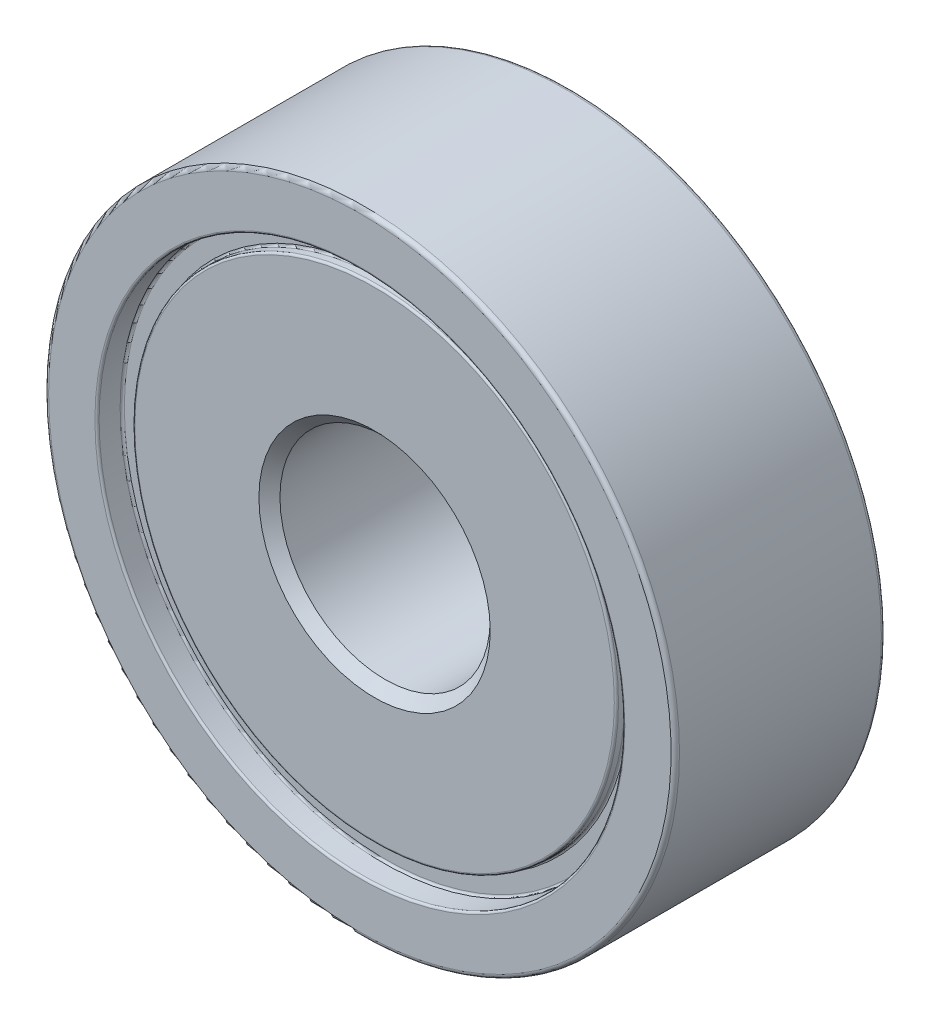
SolidWorks part; units mm, degrees
ref_plane "Front Plane" through (0, 0, 0) normal (0, 0, 1) x (1, 0, 0)
ref_plane "Top Plane" through (0, 0, 0) normal (0, 1, 0) x (1, 0, 0)
ref_plane "Right Plane" through (0, 0, 0) normal (1, 0, 0) x (0, 0, -1)
sketch "Sketch1" plane through (0, 0, 0) normal (1, 0, 0) x (0, 0, -1)
  line L0 (0.07, 0.5) -> (0.07, 1.15)
  line L1 (0.12, 1.15) -> (0.07, 1.15)
  line L2 (0.88, 1.15) -> (0.88, 1.25)
  line L3 (0.12, 1.25) -> (0, 1.25)
  line L4 (0, 1.25) -> (0, 1.5)
  line L5 (0, 1.5) -> (1, 1.5)
  line L6 (1, 1.5) -> (1, 1.25)
  line L7 (1, 1.25) -> (0.88, 1.25)
  line L8 (0.12, 1.25) -> (0.12, 1.15)
  line L9 (0.88, 1.15) -> (0.93, 1.15)
  line L10 (0.93, 1.15) -> (0.93, 0.5)
  line L11 (0.93, 0.5) -> (0.07, 0.5)
  line L12 (-145.9726, 0) -> (133.2037, 0) construction
  line L13 (55, 0) -> (-55, 0) construction
  line L14 (0, 55) -> (0, -55) construction
  line L15 (0.5, 2.4499) -> (0.5, 0.1668) construction
  point P21 (0.5, 1.5)
  dimension "D1" = 1
  dimension "D2" = 0.07
  dimension "D3" = 0.65
  dimension "D4" = 3
  dimension "D5" = 1
  dimension "D6" = 0.05
  dimension "D7" = 0.1
revolve "Revolve1" add sketch "Sketch1" angle 360 about L12
fillet "Fillet1" radius 0.01 8 edges at (1.25, 0, 0) (1.15, 0, -0.12) (1.25, 0, -0.12) (1.15, 0, -0.07) (1.15, 0, -0.88) (1.15, 0, -0.93) (1.25, 0, -1) (1.25, 0, -0.88)
chamfer "Chamfer1" distance 0.05 angle 45 2 edges at (0.5, 0, -0.93) (0.5, 0, -0.07)
fillet "Fillet2" radius 0.02 2 edges at (1.5, 0, 0) (1.5, 0, -1)
